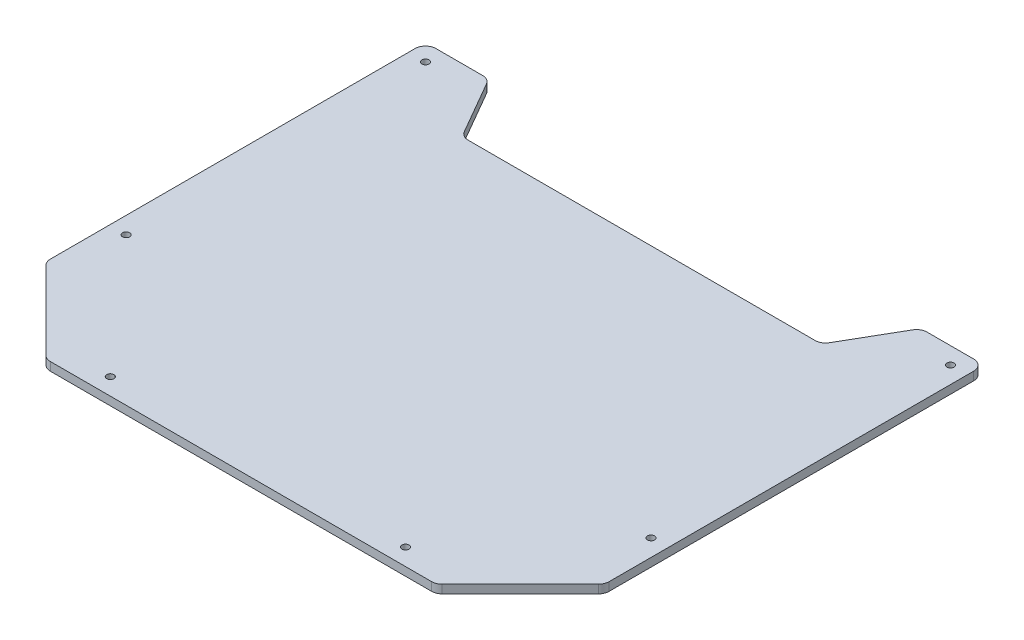
SolidWorks part; units mm, degrees
ref_plane "Front" through (0, 0, 0) normal (0, 0, 1) x (1, 0, 0)
ref_plane "Top" through (0, 0, 0) normal (0, 1, 0) x (1, 0, 0)
ref_plane "Right" through (0, 0, 0) normal (1, 0, 0) x (0, 0, -1)
sketch "Esquisse1" plane through (0, 0, 0) normal (0, 1, 0) x (1, 0, 0)
  line L0 (-92.5, 0) -> (92.5, 0)
  line L1 (0, 0) -> (132.5, 0) construction
  line L2 (0, 0) -> (0, 220) construction
  line L3 (0, 220) -> (132.5, 220) construction
  line L4 (132.5, 0) -> (132.5, 220) construction
  line L5 (92.5, 0) -> (132.5, 40)
  line L6 (132.5, 40) -> (132.5, 220)
  line L7 (132.5, 220) -> (102.5, 220)
  line L8 (102.5, 220) -> (85.1795, 190)
  line L9 (85.1795, 190) -> (-85.1795, 190)
  line L10 (-102.5, 220) -> (-85.1795, 190)
  line L11 (-132.5, 220) -> (-102.5, 220)
  line L12 (-132.5, 40) -> (-132.5, 220)
  line L13 (-92.5, 0) -> (-132.5, 40)
  point P11 (0, 190)
  dimension "D1" = 132.5
  dimension "D2" = 220
  dimension "D3" = 40
  dimension "D4" = 30
  dimension "D5" = 60
  dimension "D6" = 30
  dimension "D7" = 40
extrude "Boss.-Extru.1" add sketch "Esquisse1" along normal blind 4
sketch "Esquisse2" plane through (0, 4, 0) normal (0, 1, 0) x (1, 0, 0)
  line L0 (-92.5, 0) -> (92.5, 0) construction
  line L1 (132.5, 40) -> (132.5, 220) construction
  line L2 (132.5, 220) -> (102.5, 220) construction
  line L3 (0, 0) -> (0, 127.1828) construction
  circle A0 centre (70, 8) radius 1
  circle A1 centre (124.5, 70) radius 1
  circle A2 centre (124.5, 212) radius 1
  circle A3 centre (-70, 8) radius 1
  circle A4 centre (-124.5, 70) radius 1
  circle A5 centre (-124.5, 212) radius 1
  dimension "D3" = 2
  dimension "D6" = 2
  dimension "D9" = 2
  dimension "D1" = 70
  dimension "D2" = 8
  dimension "D4" = 70
  dimension "D5" = 8
  dimension "D7" = 8
  dimension "D8" = 8
extrude "Enlèv. mat.-Extru.1" cut sketch "Esquisse2" against normal through all
hole_wizard "Dégagement M31" positions "Esquisse3" profile "Esquisse4" hole size "M3" standard "ISO"
sketch "Esquisse3" plane through (0, 4, 0) normal (0, 1, 0) x (1, 0, 0)
  point P0 (-70, 8)
  point P3 (70, 8)
  point P6 (124.5, 70)
  point P9 (124.5, 212)
  point P12 (-124.5, 212)
  point P15 (-124.5, 70)
sketch "Esquisse4" plane through (-70, 4, -8) normal (1, 0, 0) x (0, 0, 1)
  line L0 (0, 0) -> (0, 11.0215)
  line L1 (0, 11.0215) -> (1.7, 10)
  line L2 (1.7, 10) -> (1.7, 0)
  line L5 (1.7, 0) -> (0, 0)
  line L10 (0, 11.0215) -> (-1.7, 10) construction
  line L11 (0, -6.35) -> (0, 107.95) construction
  dimension "Diamètre du perçage" = 3.4
  dimension "Profondeur du perçage" = 10
  dimension "Angle de pointe" = 118
fillet "Congé1" radius 5 10 edges at (132.5, 2, -40) (92.5, 2, 0) (-92.5, 2, 0) (-132.5, 2, -40) (-132.5, 2, -220) (-102.5, 2, -220) (-85.1795, 2, -190) (85.1795, 2, -190) (102.5, 2, -220) (132.5, 2, -220)
